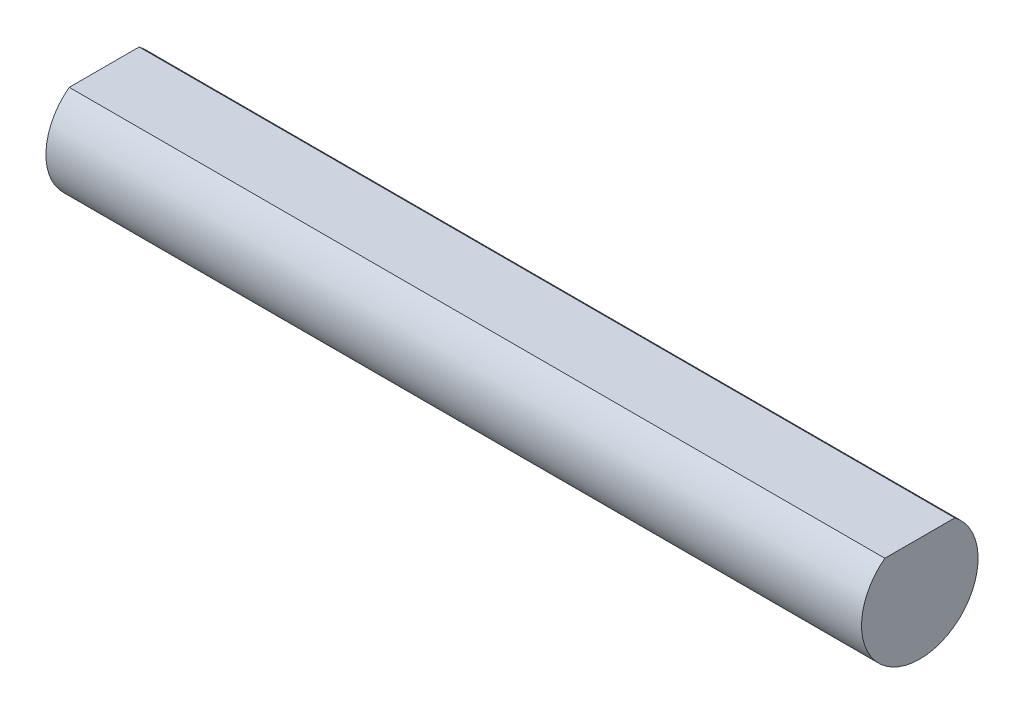
SolidWorks part; units mm, degrees
material "AISI 1045 Steel, cold drawn"
ref_plane "Front Plane" through (0, 0, 0) normal (0, 0, 1) x (1, 0, 0)
ref_plane "Top Plane" through (0, 0, 0) normal (0, 1, 0) x (1, 0, 0)
ref_plane "Right Plane" through (0, 0, 0) normal (1, 0, 0) x (0, 0, -1)
sketch "Sketch1" plane through (0, 0, 0) normal (1, 0, 0) x (0, 0, -1)
  line L0 (-1.905, 2.54) -> (1.905, 2.54)
  arc A0 (-1.905, 2.54) -> (1.905, 2.54) centre (0, 0) ccw
  dimension "D1" = 6.35
  dimension "D2" = 2.54
extrude "Boss-Extrude1" add sketch "Sketch1" along normal mid plane 44.45
sketch "Sketch2" [suppressed] plane through (22.225, 0, 0) normal (1, 0, 0) x (0, 0, -1)
  line L1 (1.905, 2.54) -> (-1.905, 2.54)
  line L2 (1.905, 2.54) -> (-1.905, 2.54)
  arc A1 (-1.905, 2.54) -> (1.905, 2.54) centre (0, 0) ccw
  arc A2 (-1.905, 2.54) -> (1.905, 2.54) centre (0, 0) ccw
  dimension "D1" = 0
extrude "Boss-Extrude2" [suppressed] add sketch "Sketch2" along normal blind 16.51
